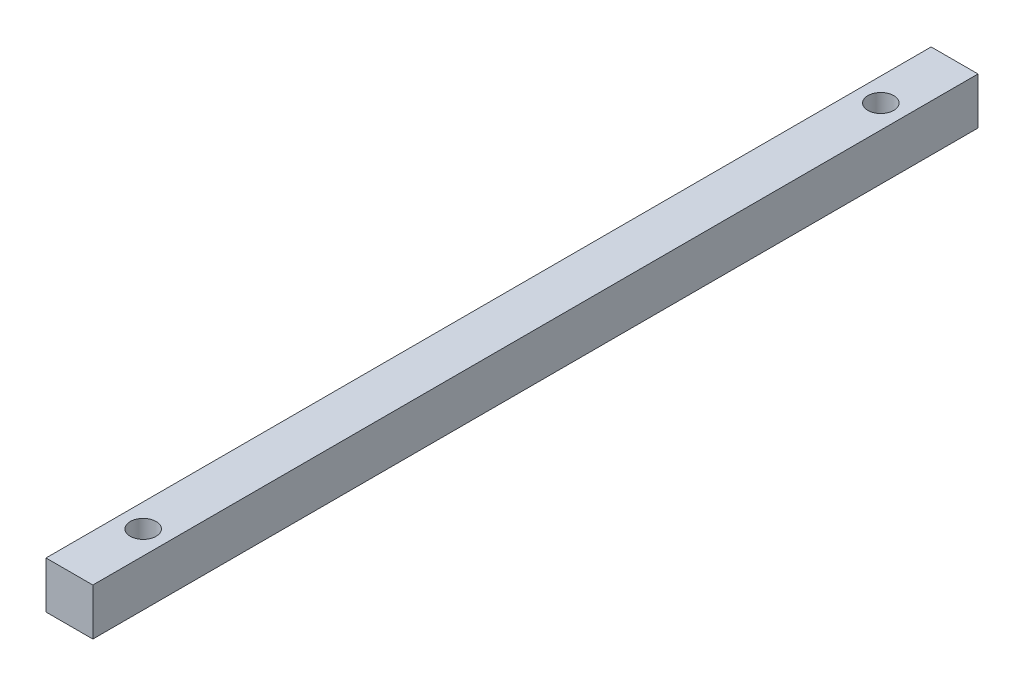
SolidWorks part; units mm, degrees
ref_plane "Front Plane" through (0, 0, 0) normal (0, 0, 1) x (1, 0, 0)
ref_plane "Top Plane" through (0, 0, 0) normal (0, 1, 0) x (1, 0, 0)
ref_plane "Right Plane" through (0, 0, 0) normal (1, 0, 0) x (0, 0, -1)
sketch "Sketch1" plane through (0, 0, 0) normal (0, 0, 1) x (1, 0, 0)
  line L0 (-3.175, 3.175) -> (-3.175, -3.175) construction
  line L1 (-3.175, 3.175) -> (3.175, 3.175) construction
  line L2 (-3.175, 0) -> (0, 0) construction
  line L3 (0, 0) -> (0, 3.175) construction
  dimension "Thickness" = 6.35
  dimension "Width" = 6.35
ref_plane "Plane1" through (-3.175, 3.175, 0) normal (0, -1, 0) x (-1, 0, 0)
sketch "Sketch2" plane through (-3.175, 3.175, 0) normal (0, 1, 0) x (1, 0, 0)
  line L0 (3.175, -609.6) -> (3.175, 609.6) construction
  point P2 (3.175, -596.9)
  point P3 (3.175, 596.9)
  dimension "Length" = 1219.2
  dimension "D1" = 12.7
  dimension "D2" = 12.7
sketch "Sketch3" plane through (0, 0, 0) normal (0, 0, 1) x (1, 0, 0)
  line L1 (-3.175, -3.175) -> (3.175, -3.175)
  line L2 (-3.175, -3.175) -> (-3.175, 3.175)
  line L3 (-3.175, 3.175) -> (3.175, 3.175)
  line L4 (3.175, -3.175) -> (3.175, 3.175)
  line L5 (0, 3.175) -> (0, -3.175) construction
  line L6 (-3.175, 0) -> (3.175, 0) construction
  line L7 (-3.175, 0) -> (0, 0) construction
extrude "Boss-Extrude1" add sketch "Sketch3" along normal up to vertex (609.6 mm away) and the other way up to vertex (609.6 mm away) up to point (0, 3.175, 609.6) other way up to point (0, 3.175, -609.6)
ref_plane "Plane2" through (0, 0, -489.6) normal (0, 0, -1) x (-1, 0, 0)
sketch "Sketch4" plane through (0, 0, -489.6) normal (0, 0, -1) x (-1, 0, 0)
  line L0 (-3.175, -3.175) -> (-3.175, 3.175) construction
  line L1 (-3.675, 3.675) -> (3.675, 3.675)
  line L2 (-3.675, 3.675) -> (-3.675, -3.675)
  line L3 (-3.675, -3.675) -> (3.675, -3.675)
  line L4 (3.675, 3.675) -> (3.675, -3.675)
  line L5 (-3.675, 3.675) -> (3.675, -3.675) construction
  line L6 (-3.675, -3.675) -> (3.675, 3.675) construction
  point P0 (0, 0)
  dimension "D1" = 0.5
extrude "Cut-Extrude1" cut sketch "Sketch4" against normal through all
sketch "Sketch5" plane through (0, 3.175, 0) normal (0, 1, 0) x (1, 0, 0)
  line L0 (3.175, 609.6) -> (-3.175, 609.6) construction
  line L1 (-3.175, 489.6) -> (3.175, 489.6) construction
  line L2 (3.175, 489.6) -> (3.175, 609.6) construction
  circle A0 centre (0, 599.6) radius 1.75
  circle A1 centre (0, 499.6) radius 1.75
  dimension "D2" = 3.5
  dimension "D1" = 10
  dimension "D3" = 10
  dimension "D4" = 3.175
extrude "Cut-Extrude2" cut sketch "Sketch5" against normal through all
equation "\"D1@Sketch2\"=\"Width@Sketch1\"*2"
equation "\"D2@Sketch2\"=\"D1@Sketch2\""
